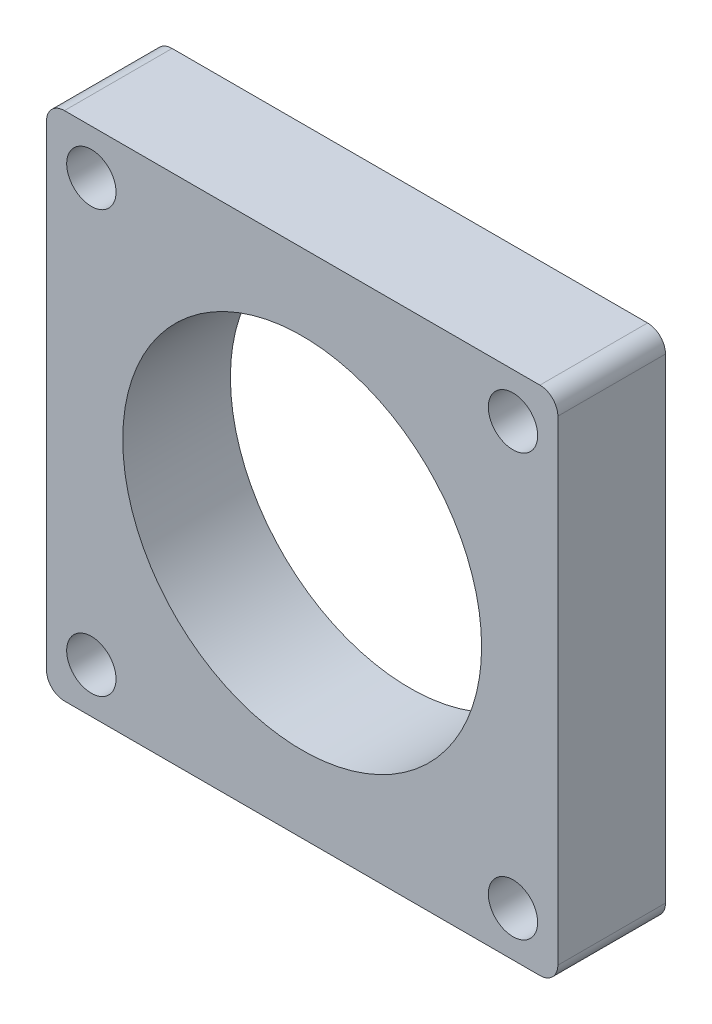
SolidWorks part; units mm, degrees
ref_plane "Front Plane" through (0, 0, 0) normal (0, 0, 1) x (1, 0, 0)
ref_plane "Top Plane" through (0, 0, 0) normal (0, 1, 0) x (1, 0, 0)
ref_plane "Right Plane" through (0, 0, 0) normal (1, 0, 0) x (0, 0, -1)
sketch "Sketch1" plane through (0, 0, 0) normal (0, 0, 1) x (1, 0, 0)
  line L1 (-28.5, 28.5) -> (28.5, 28.5)
  line L2 (-28.5, 28.5) -> (-28.5, -28.5)
  line L3 (-28.5, -28.5) -> (28.5, -28.5)
  line L4 (28.5, 28.5) -> (28.5, -28.5)
  line L5 (-28.5, 28.5) -> (28.5, -28.5) construction
  line L6 (-28.5, -28.5) -> (28.5, 28.5) construction
  circle A0 centre (-23.5, 23.5) radius 2.75
  circle A1 centre (23.5, 23.5) radius 2.75
  circle A2 centre (23.5, -23.5) radius 2.75
  circle A3 centre (-23.5, -23.5) radius 2.75
  circle A4 centre (0, 0) radius 20
  point P0 (0, 0)
  dimension "D3" = 47
  dimension "D4" = 47
  dimension "D5" = 47
  dimension "D6" = 5.5
  dimension "D7" = 5.5
  dimension "D8" = 5.5
  dimension "D9" = 5.5
  dimension "D10" = 40
  dimension "D11" = 47
  dimension "D1" = 57
  dimension "D2" = 57
extrude "Boss-Extrude1" add sketch "Sketch1" along normal blind 12
fillet "Fillet1" radius 2 4 edges at (-28.5, -28.5, 6) (28.5, -28.5, 6) (28.5, 28.5, 6) (-28.5, 28.5, 6)
